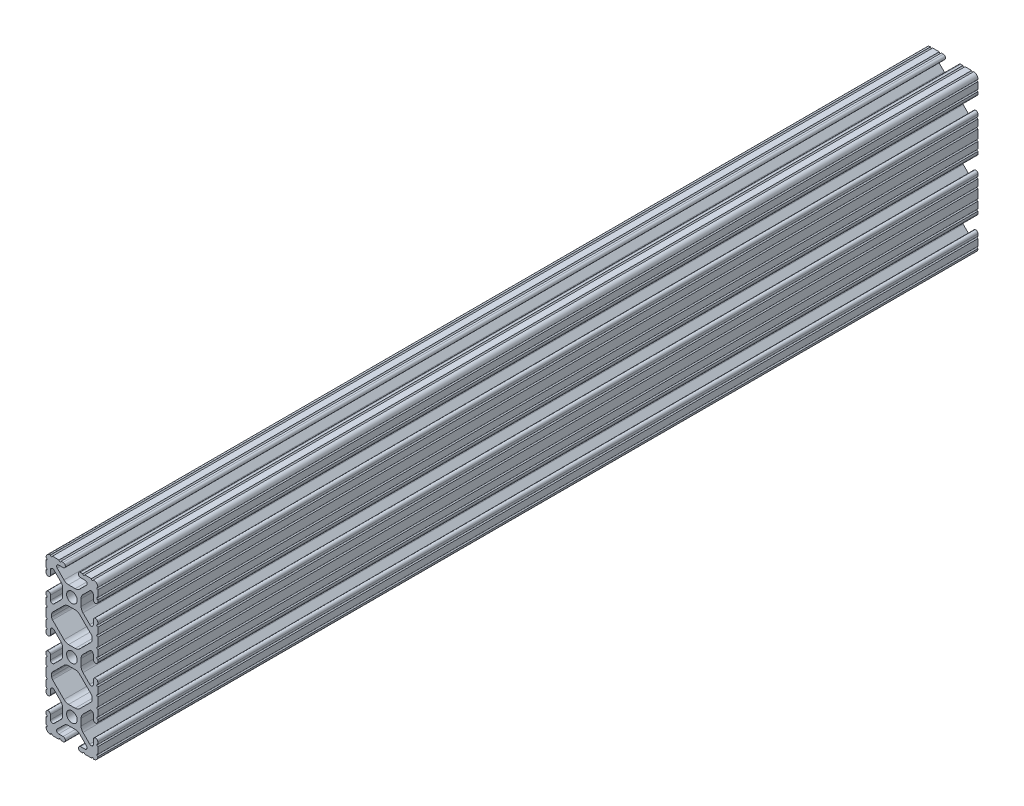
SolidWorks part; units mm, degrees
ref_plane "Front Plane" through (0, 0, 0) normal (0, 0, 1) x (1, 0, 0)
ref_plane "Top Plane" through (0, 0, 0) normal (0, 1, 0) x (1, 0, 0)
ref_plane "Right Plane" through (0, 0, 0) normal (1, 0, 0) x (0, 0, -1)
sketch "Sketch1" plane through (0, 0, 0) normal (0, 0, 1) x (1, 0, 0)
  line L0 (-9.9314, 12.1463) -> (-9.9314, 13.2537)
  line L1 (-9.4702, 14.3673) -> (-3.8759, 19.9616)
  line L2 (-1.6308, 20.8915) -> (1.6308, 20.8915)
  line L3 (3.8759, 19.9616) -> (9.4702, 14.3673)
  line L4 (9.9314, 13.2537) -> (9.9314, 12.1463)
  line L5 (9.4702, 11.0327) -> (3.8759, 5.4384)
  line L6 (1.6308, 4.5085) -> (-1.6308, 4.5085)
  line L7 (-3.8759, 5.4384) -> (-9.4702, 11.0327)
  line L8 (-9.9314, -13.2537) -> (-9.9314, -12.1463)
  line L9 (-9.4702, -11.0327) -> (-3.8759, -5.4384)
  line L10 (-1.6308, -4.5085) -> (1.6308, -4.5085)
  line L11 (3.8759, -5.4384) -> (9.4702, -11.0327)
  line L12 (9.9314, -12.1463) -> (9.9314, -13.2537)
  line L13 (9.4702, -14.3673) -> (3.8759, -19.9616)
  line L14 (1.6308, -20.8915) -> (-1.6308, -20.8915)
  line L15 (-3.8759, -19.9616) -> (-9.4702, -14.3673)
  line L16 (-6.3246, 38.1) -> (-9.5504, 38.1)
  line L17 (-12.7, 34.9504) -> (-12.7, 31.7246)
  line L18 (-12.7, 30.7086) -> (-12.7, 29.7023)
  line L19 (-10.4902, 29.7023) -> (-10.4902, 31.8748)
  line L20 (-8.7558, 32.5932) -> (-5.4384, 29.2759)
  line L21 (-4.5085, 27.0308) -> (-4.5085, 23.7692)
  line L22 (-5.4384, 21.5241) -> (-8.7558, 18.2068)
  line L23 (-10.4902, 18.9252) -> (-10.4902, 21.0977)
  line L24 (-12.7, 21.0977) -> (-12.7, 20.0914)
  line L25 (-12.7, 19.0754) -> (-12.7, 15.8496)
  line L26 (-12.7, 14.8336) -> (-12.7, 10.5664)
  line L27 (-12.7, 9.5504) -> (-12.7, 6.3246)
  line L28 (-12.7, 5.3086) -> (-12.7, 4.3023)
  line L29 (-10.4902, 4.3023) -> (-10.4902, 6.4748)
  line L30 (-8.7558, 7.1932) -> (-5.4384, 3.8759)
  line L31 (-4.5085, 1.6308) -> (-4.5085, -1.6308)
  line L32 (-5.4384, -3.8759) -> (-8.7558, -7.1932)
  line L33 (-10.4902, -6.4748) -> (-10.4902, -4.3023)
  line L34 (-12.7, -4.3023) -> (-12.7, -5.3086)
  line L35 (-12.7, -6.3246) -> (-12.7, -9.5504)
  line L36 (-12.7, -10.5664) -> (-12.7, -14.8336)
  line L37 (-12.7, -15.8496) -> (-12.7, -19.0754)
  line L38 (-12.7, -20.0914) -> (-12.7, -21.0977)
  line L39 (-10.4902, -21.0977) -> (-10.4902, -18.9252)
  line L40 (-8.7558, -18.2068) -> (-5.4384, -21.5241)
  line L41 (-4.5085, -23.7692) -> (-4.5085, -27.0308)
  line L42 (-5.4384, -29.2759) -> (-8.7558, -32.5932)
  line L43 (-10.4902, -31.8748) -> (-10.4902, -29.7023)
  line L44 (-12.7, -29.7023) -> (-12.7, -30.7086)
  line L45 (-12.7, -31.7246) -> (-12.7, -34.9504)
  line L46 (-9.5504, -38.1) -> (-6.3246, -38.1)
  line L47 (-5.3086, -38.1) -> (-4.3023, -38.1)
  line L48 (-4.3023, -35.8902) -> (-6.4748, -35.8902)
  line L49 (-7.1932, -34.1558) -> (-3.8759, -30.8384)
  line L50 (-1.6308, -29.9085) -> (1.6308, -29.9085)
  line L51 (3.8759, -30.8384) -> (7.1932, -34.1558)
  line L52 (6.4748, -35.8902) -> (4.3023, -35.8902)
  line L53 (4.3023, -38.1) -> (5.3086, -38.1)
  line L54 (6.3246, -38.1) -> (9.5504, -38.1)
  line L55 (12.7, -34.9504) -> (12.7, -31.7246)
  line L56 (12.7, -30.7086) -> (12.7, -29.7023)
  line L57 (10.4902, -29.7023) -> (10.4902, -31.8748)
  line L58 (8.7558, -32.5932) -> (5.4384, -29.2759)
  line L59 (4.5085, -27.0308) -> (4.5085, -23.7692)
  line L60 (5.4384, -21.5241) -> (8.7558, -18.2068)
  line L61 (10.4902, -18.9252) -> (10.4902, -21.0977)
  line L62 (12.7, -21.0977) -> (12.7, -20.0914)
  line L63 (12.7, -19.0754) -> (12.7, -15.8496)
  line L64 (12.7, -14.8336) -> (12.7, -10.5664)
  line L65 (12.7, -9.5504) -> (12.7, -6.3246)
  line L66 (12.7, -5.3086) -> (12.7, -4.3023)
  line L67 (10.4902, -4.3023) -> (10.4902, -6.4748)
  line L68 (8.7558, -7.1932) -> (5.4384, -3.8759)
  line L69 (4.5085, -1.6308) -> (4.5085, 1.6308)
  line L70 (5.4384, 3.8759) -> (8.7558, 7.1932)
  line L71 (10.4902, 6.4748) -> (10.4902, 4.3023)
  line L72 (12.7, 4.3023) -> (12.7, 5.3086)
  line L73 (12.7, 6.3246) -> (12.7, 9.5504)
  line L74 (12.7, 10.5664) -> (12.7, 14.8336)
  line L75 (12.7, 15.8496) -> (12.7, 19.0754)
  line L76 (12.7, 20.0914) -> (12.7, 21.0977)
  line L77 (10.4902, 21.0977) -> (10.4902, 18.9252)
  line L78 (8.7558, 18.2068) -> (5.4384, 21.5241)
  line L79 (4.5085, 23.7692) -> (4.5085, 27.0308)
  line L80 (5.4384, 29.2759) -> (8.7558, 32.5932)
  line L81 (10.4902, 31.8748) -> (10.4902, 29.7023)
  line L82 (12.7, 29.7023) -> (12.7, 30.7086)
  line L83 (12.7, 31.7246) -> (12.7, 34.9504)
  line L84 (9.5504, 38.1) -> (6.3246, 38.1)
  line L85 (5.3086, 38.1) -> (4.3023, 38.1)
  line L86 (4.3023, 35.8902) -> (6.4748, 35.8902)
  line L87 (7.1932, 34.1558) -> (3.8759, 30.8384)
  line L88 (1.6308, 29.9085) -> (-1.6308, 29.9085)
  line L89 (-3.8759, 30.8384) -> (-7.1932, 34.1558)
  line L90 (-6.4748, 35.8902) -> (-4.3023, 35.8902)
  line L91 (-4.3023, 38.1) -> (-5.3086, 38.1)
  circle A0 centre (0, 25.4) radius 2.6035
  arc A1 (-9.9314, 13.2537) -> (-9.4702, 14.3673) centre (-8.3566, 13.2537) cw
  arc A2 (-3.8759, 19.9616) -> (-1.6308, 20.8915) centre (-1.6308, 17.7165) cw
  arc A3 (1.6308, 20.8915) -> (3.8759, 19.9616) centre (1.6308, 17.7165) cw
  arc A4 (9.4702, 14.3673) -> (9.9314, 13.2537) centre (8.3566, 13.2537) cw
  arc A5 (9.9314, 12.1463) -> (9.4702, 11.0327) centre (8.3566, 12.1463) cw
  arc A6 (3.8759, 5.4384) -> (1.6308, 4.5085) centre (1.6308, 7.6835) cw
  arc A7 (-1.6308, 4.5085) -> (-3.8759, 5.4384) centre (-1.6308, 7.6835) cw
  arc A8 (-9.4702, 11.0327) -> (-9.9314, 12.1463) centre (-8.3566, 12.1463) cw
  arc A9 (-9.9314, -12.1463) -> (-9.4702, -11.0327) centre (-8.3566, -12.1463) cw
  arc A10 (-3.8759, -5.4384) -> (-1.6308, -4.5085) centre (-1.6308, -7.6835) cw
  arc A11 (1.6308, -4.5085) -> (3.8759, -5.4384) centre (1.6308, -7.6835) cw
  arc A12 (9.4702, -11.0327) -> (9.9314, -12.1463) centre (8.3566, -12.1463) cw
  arc A13 (9.9314, -13.2537) -> (9.4702, -14.3673) centre (8.3566, -13.2537) cw
  arc A14 (3.8759, -19.9616) -> (1.6308, -20.8915) centre (1.6308, -17.7165) cw
  arc A15 (-1.6308, -20.8915) -> (-3.8759, -19.9616) centre (-1.6308, -17.7165) cw
  arc A16 (-9.4702, -14.3673) -> (-9.9314, -13.2537) centre (-8.3566, -13.2537) cw
  circle A17 centre (0, -25.4) radius 2.6035
  circle A18 centre (0, 0) radius 2.6035
  arc A19 (-5.3086, 38.1) -> (-6.3246, 38.1) centre (-5.8166, 38.1) cw
  arc A20 (-9.5504, 38.1) -> (-10.5664, 38.1) centre (-10.0584, 38.1) cw
  arc A21 (-10.5664, 38.1) -> (-12.7, 35.9664) centre (-10.592, 35.992) ccw
  arc A22 (-12.7, 35.9664) -> (-12.7, 34.9504) centre (-12.7, 35.4584) cw
  arc A23 (-12.7, 31.7246) -> (-12.7, 30.7086) centre (-12.7, 31.2166) cw
  arc A24 (-12.7, 29.7023) -> (-10.4902, 29.7023) centre (-11.5951, 29.7023) ccw
  arc A25 (-10.4902, 31.8748) -> (-8.7558, 32.5932) centre (-9.4742, 31.8748) cw
  arc A26 (-5.4384, 29.2759) -> (-4.5085, 27.0308) centre (-7.6835, 27.0308) cw
  arc A27 (-4.5085, 23.7692) -> (-5.4384, 21.5241) centre (-7.6835, 23.7692) cw
  arc A28 (-8.7558, 18.2068) -> (-10.4902, 18.9252) centre (-9.4742, 18.9252) cw
  arc A29 (-10.4902, 21.0977) -> (-12.7, 21.0977) centre (-11.5951, 21.0977) ccw
  arc A30 (-12.7, 20.0914) -> (-12.7, 19.0754) centre (-12.7, 19.5834) cw
  arc A31 (-12.7, 15.8496) -> (-12.7, 14.8336) centre (-12.7, 15.3416) cw
  arc A32 (-12.7, 10.5664) -> (-12.7, 9.5504) centre (-12.7, 10.0584) cw
  arc A33 (-12.7, 6.3246) -> (-12.7, 5.3086) centre (-12.7, 5.8166) cw
  arc A34 (-12.7, 4.3023) -> (-10.4902, 4.3023) centre (-11.5951, 4.3023) ccw
  arc A35 (-10.4902, 6.4748) -> (-8.7558, 7.1932) centre (-9.4742, 6.4748) cw
  arc A36 (-5.4384, 3.8759) -> (-4.5085, 1.6308) centre (-7.6835, 1.6308) cw
  arc A37 (-4.5085, -1.6308) -> (-5.4384, -3.8759) centre (-7.6835, -1.6308) cw
  arc A38 (-8.7558, -7.1932) -> (-10.4902, -6.4748) centre (-9.4742, -6.4748) cw
  arc A39 (-10.4902, -4.3023) -> (-12.7, -4.3023) centre (-11.5951, -4.3023) ccw
  arc A40 (-12.7, -5.3086) -> (-12.7, -6.3246) centre (-12.7, -5.8166) cw
  arc A41 (-12.7, -9.5504) -> (-12.7, -10.5664) centre (-12.7, -10.0584) cw
  arc A42 (-12.7, -14.8336) -> (-12.7, -15.8496) centre (-12.7, -15.3416) cw
  arc A43 (-12.7, -19.0754) -> (-12.7, -20.0914) centre (-12.7, -19.5834) cw
  arc A44 (-12.7, -21.0977) -> (-10.4902, -21.0977) centre (-11.5951, -21.0977) ccw
  arc A45 (-10.4902, -18.9252) -> (-8.7558, -18.2068) centre (-9.4742, -18.9252) cw
  arc A46 (-5.4384, -21.5241) -> (-4.5085, -23.7692) centre (-7.6835, -23.7692) cw
  arc A47 (-4.5085, -27.0308) -> (-5.4384, -29.2759) centre (-7.6835, -27.0308) cw
  arc A48 (-8.7558, -32.5932) -> (-10.4902, -31.8748) centre (-9.4742, -31.8748) cw
  arc A49 (-10.4902, -29.7023) -> (-12.7, -29.7023) centre (-11.5951, -29.7023) ccw
  arc A50 (-12.7, -30.7086) -> (-12.7, -31.7246) centre (-12.7, -31.2166) cw
  arc A51 (-12.7, -34.9504) -> (-12.7, -35.9664) centre (-12.7, -35.4584) cw
  arc A52 (-12.7, -35.9664) -> (-10.5664, -38.1) centre (-10.592, -35.992) ccw
  arc A53 (-10.5664, -38.1) -> (-9.5504, -38.1) centre (-10.0584, -38.1) cw
  arc A54 (-6.3246, -38.1) -> (-5.3086, -38.1) centre (-5.8166, -38.1) cw
  arc A55 (-4.3023, -38.1) -> (-4.3023, -35.8902) centre (-4.3023, -36.9951) ccw
  arc A56 (-6.4748, -35.8902) -> (-7.1932, -34.1558) centre (-6.4748, -34.8742) cw
  arc A57 (-3.8759, -30.8384) -> (-1.6308, -29.9085) centre (-1.6308, -33.0835) cw
  arc A58 (1.6308, -29.9085) -> (3.8759, -30.8384) centre (1.6308, -33.0835) cw
  arc A59 (7.1932, -34.1558) -> (6.4748, -35.8902) centre (6.4748, -34.8742) cw
  arc A60 (4.3023, -35.8902) -> (4.3023, -38.1) centre (4.3023, -36.9951) ccw
  arc A61 (5.3086, -38.1) -> (6.3246, -38.1) centre (5.8166, -38.1) cw
  arc A62 (9.5504, -38.1) -> (10.5664, -38.1) centre (10.0584, -38.1) cw
  arc A63 (10.5664, -38.1) -> (12.7, -35.9664) centre (10.592, -35.992) ccw
  arc A64 (12.7, -35.9664) -> (12.7, -34.9504) centre (12.7, -35.4584) cw
  arc A65 (12.7, -31.7246) -> (12.7, -30.7086) centre (12.7, -31.2166) cw
  arc A66 (12.7, -29.7023) -> (10.4902, -29.7023) centre (11.5951, -29.7023) ccw
  arc A67 (10.4902, -31.8748) -> (8.7558, -32.5932) centre (9.4742, -31.8748) cw
  arc A68 (5.4384, -29.2759) -> (4.5085, -27.0308) centre (7.6835, -27.0308) cw
  arc A69 (4.5085, -23.7692) -> (5.4384, -21.5241) centre (7.6835, -23.7692) cw
  arc A70 (8.7558, -18.2068) -> (10.4902, -18.9252) centre (9.4742, -18.9252) cw
  arc A71 (10.4902, -21.0977) -> (12.7, -21.0977) centre (11.5951, -21.0977) ccw
  arc A72 (12.7, -20.0914) -> (12.7, -19.0754) centre (12.7, -19.5834) cw
  arc A73 (12.7, -15.8496) -> (12.7, -14.8336) centre (12.7, -15.3416) cw
  arc A74 (12.7, -10.5664) -> (12.7, -9.5504) centre (12.7, -10.0584) cw
  arc A75 (12.7, -6.3246) -> (12.7, -5.3086) centre (12.7, -5.8166) cw
  arc A76 (12.7, -4.3023) -> (10.4902, -4.3023) centre (11.5951, -4.3023) ccw
  arc A77 (10.4902, -6.4748) -> (8.7558, -7.1932) centre (9.4742, -6.4748) cw
  arc A78 (5.4384, -3.8759) -> (4.5085, -1.6308) centre (7.6835, -1.6308) cw
  arc A79 (4.5085, 1.6308) -> (5.4384, 3.8759) centre (7.6835, 1.6308) cw
  arc A80 (8.7558, 7.1932) -> (10.4902, 6.4748) centre (9.4742, 6.4748) cw
  arc A81 (10.4902, 4.3023) -> (12.7, 4.3023) centre (11.5951, 4.3023) ccw
  arc A82 (12.7, 5.3086) -> (12.7, 6.3246) centre (12.7, 5.8166) cw
  arc A83 (12.7, 9.5504) -> (12.7, 10.5664) centre (12.7, 10.0584) cw
  arc A84 (12.7, 14.8336) -> (12.7, 15.8496) centre (12.7, 15.3416) cw
  arc A85 (12.7, 19.0754) -> (12.7, 20.0914) centre (12.7, 19.5834) cw
  arc A86 (12.7, 21.0977) -> (10.4902, 21.0977) centre (11.5951, 21.0977) ccw
  arc A87 (10.4902, 18.9252) -> (8.7558, 18.2068) centre (9.4742, 18.9252) cw
  arc A88 (5.4384, 21.5241) -> (4.5085, 23.7692) centre (7.6835, 23.7692) cw
  arc A89 (4.5085, 27.0308) -> (5.4384, 29.2759) centre (7.6835, 27.0308) cw
  arc A90 (8.7558, 32.5932) -> (10.4902, 31.8748) centre (9.4742, 31.8748) cw
  arc A91 (10.4902, 29.7023) -> (12.7, 29.7023) centre (11.5951, 29.7023) ccw
  arc A92 (12.7, 30.7086) -> (12.7, 31.7246) centre (12.7, 31.2166) cw
  arc A93 (12.7, 34.9504) -> (12.7, 35.9664) centre (12.7, 35.4584) cw
  arc A94 (12.7, 35.9664) -> (10.5664, 38.1) centre (10.592, 35.992) ccw
  arc A95 (10.5664, 38.1) -> (9.5504, 38.1) centre (10.0584, 38.1) cw
  arc A96 (6.3246, 38.1) -> (5.3086, 38.1) centre (5.8166, 38.1) cw
  arc A97 (4.3023, 38.1) -> (4.3023, 35.8902) centre (4.3023, 36.9951) ccw
  arc A98 (6.4748, 35.8902) -> (7.1932, 34.1558) centre (6.4748, 34.8742) cw
  arc A99 (3.8759, 30.8384) -> (1.6308, 29.9085) centre (1.6308, 33.0835) cw
  arc A100 (-1.6308, 29.9085) -> (-3.8759, 30.8384) centre (-1.6308, 33.0835) cw
  arc A101 (-7.1932, 34.1558) -> (-6.4748, 35.8902) centre (-6.4748, 34.8742) cw
  arc A102 (-4.3023, 35.8902) -> (-4.3023, 38.1) centre (-4.3023, 36.9951) ccw
extrude "Boss-Extrude1" add sketch "Sketch1" against normal blind 431.8
